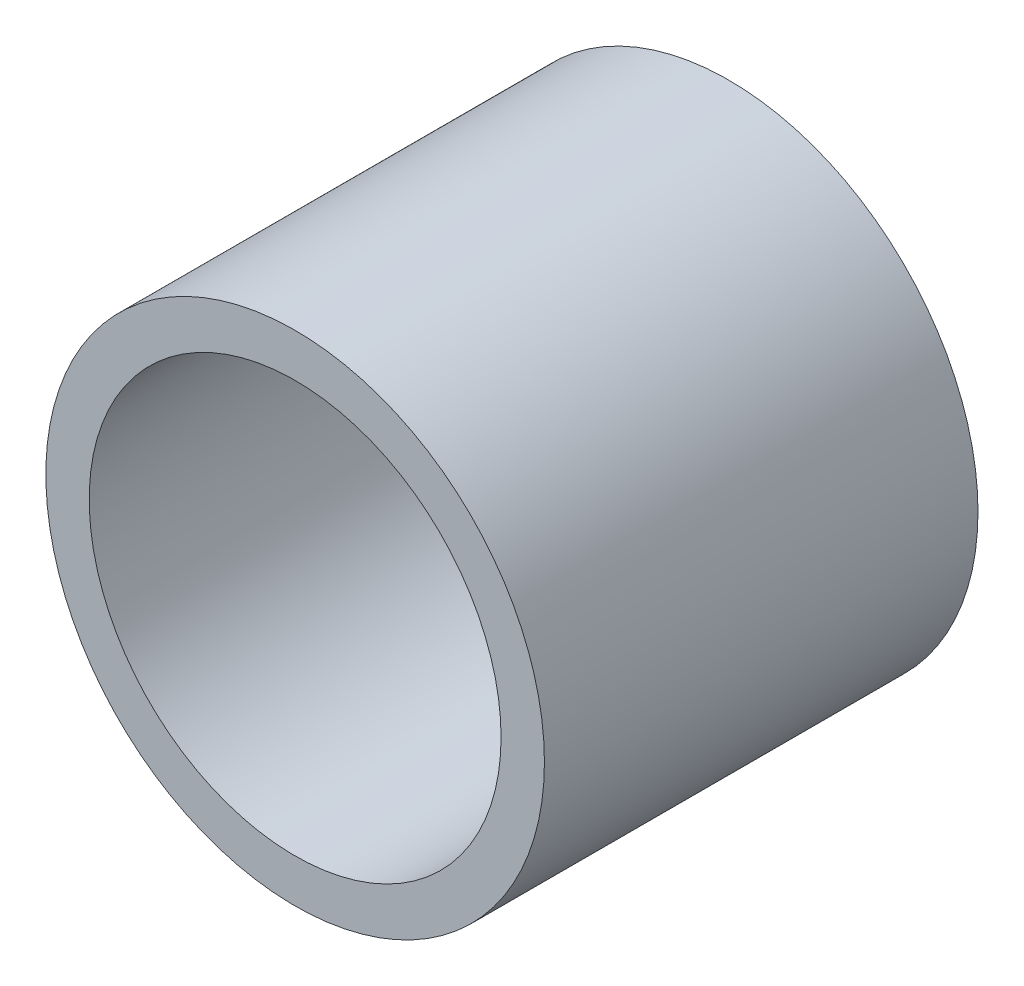
SolidWorks part; units mm, degrees
ref_plane "Front Plane" through (0, 0, 0) normal (0, 0, 1) x (1, 0, 0)
ref_plane "Top Plane" through (0, 0, 0) normal (0, 1, 0) x (1, 0, 0)
ref_plane "Right Plane" through (0, 0, 0) normal (1, 0, 0) x (0, 0, -1)
sketch "Sketch1" plane through (0, 0, 0) normal (0, 0, 1) x (1, 0, 0)
  circle A0 centre (0, 0) radius 4.75
  circle A1 centre (0, 0) radius 5.75
  dimension "D1" = 9.5
  dimension "D2" = 11.5
extrude "Boss-Extrude1" add sketch "Sketch1" along normal blind 10
